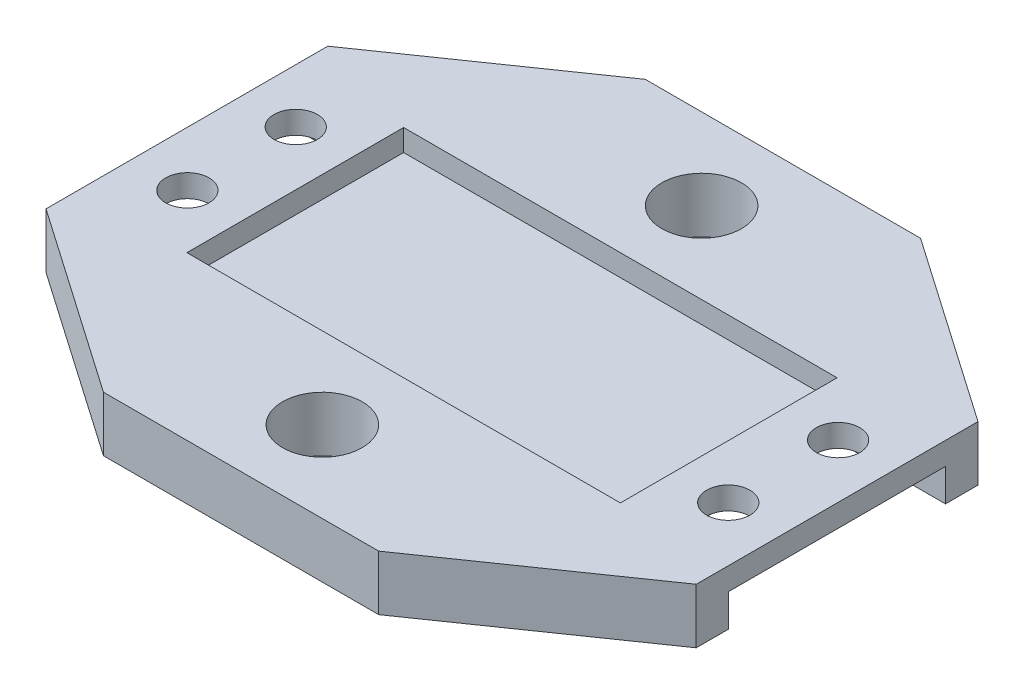
SolidWorks part; units mm, degrees
ref_plane "Front Plane" through (0, 0, 0) normal (0, 0, 1) x (1, 0, 0)
ref_plane "Top Plane" through (0, 0, 0) normal (0, 1, 0) x (1, 0, 0)
ref_plane "Right Plane" through (0, 0, 0) normal (1, 0, 0) x (0, 0, -1)
sketch "Sketch1" plane through (0, 0, 0) normal (0, 1, 0) x (1, 0, 0)
  line L0 (-48.0587, 12.2268) -> (11.9413, 12.2268) construction
  line L1 (-48.0587, 27.2268) -> (11.9413, 27.2268)
  line L2 (-48.0587, 27.2268) -> (-48.0587, -22.7732)
  line L3 (-48.0587, -22.7732) -> (11.9413, -22.7732)
  line L4 (11.9413, 27.2268) -> (11.9413, -22.7732)
  line L5 (11.9413, -7.7732) -> (-48.0587, -7.7732) construction
  line L6 (-18.0587, 27.2268) -> (-18.0587, -22.7732) construction
  dimension "D1" = 60
  dimension "D2" = 50
  dimension "D3" = 15
  dimension "D4" = 15
extrude "Boss-Extrude1" add sketch "Sketch1" along normal blind 5.08
sketch "Sketch2" plane through (0, 5.08, 0) normal (0, 1, 0) x (1, 0, 0)
  line L0 (-18.0587, 27.2268) -> (-18.0587, -22.7732) construction
  line L1 (11.9413, 27.2268) -> (-48.0587, 27.2268) construction
  line L2 (-48.0587, -22.7732) -> (11.9413, -22.7732) construction
  line L3 (-30.7587, 27.2268) -> (-5.3587, 27.2268)
  line L4 (-30.7587, 27.2268) -> (-48.0587, 15.2268)
  line L5 (-48.0587, 27.2268) -> (-48.0587, -22.7732) construction
  line L6 (-5.3587, 27.2268) -> (11.9413, 15.2268)
  line L7 (11.9413, -22.7732) -> (11.9413, 27.2268) construction
  line L8 (11.9413, 2.2268) -> (-48.0587, 2.2268) construction
  line L9 (-30.7587, -22.7732) -> (-48.0587, -10.7732)
  line L10 (-30.7587, -22.7732) -> (-5.3587, -22.7732)
  line L11 (-5.3587, -22.7732) -> (11.9413, -10.7732)
  line L12 (-48.0587, 15.2268) -> (-48.0587, -10.7732)
  line L13 (11.9413, -10.7732) -> (11.9413, 15.2268)
  circle A0 centre (-18.0587, 19.7268) radius 3.675
  circle A1 centre (-18.0587, -15.2732) radius 3.675
  point P24 (0, 0)
  dimension "D4" = 7.5
  dimension "D5" = 7.35
  dimension "D1" = 25.4
  dimension "D2" = 12
  dimension "D3" = 12
extrude "Cut-Extrude1" cut sketch "Sketch2" against normal through all flip side to cut
sketch "Sketch12" plane through (-48.0587, 0, 0) normal (-1, 0, 0) x (0, 0, 1)
  line L0 (-15.2268, 0) -> (10.7732, 0) construction
  line L1 (7.815, 0) -> (-12.185, 0)
  line L2 (7.815, 0) -> (7.815, 3)
  line L3 (7.815, 3) -> (-12.185, 3)
  line L4 (-12.185, 0) -> (-12.185, 3)
  dimension "D1" = 20
  dimension "D2" = 3
extrude "Cut-Extrude6" cut sketch "Sketch12" against normal blind 10
sketch "Sketch13" plane through (11.9413, 0, 0) normal (1, 0, 0) x (0, 0, -1)
  line L0 (-10.7732, 0) -> (15.2268, 0) construction
  line L1 (12.2268, 0) -> (-7.7732, 0)
  line L2 (12.2268, 0) -> (12.2268, 3)
  line L3 (12.2268, 3) -> (-7.7732, 3)
  line L4 (-7.7732, 0) -> (-7.7732, 3)
  dimension "D1" = 3
  dimension "D2" = 20
  dimension "D3" = 3
extrude "Cut-Extrude7" cut sketch "Sketch13" against normal blind 10
sketch "Sketch14" plane through (0, 5.08, 0) normal (0, 1, 0) x (1, 0, 0)
  line L0 (-18.0587, 27.2268) -> (-18.0587, -22.7732) construction
  line L1 (-5.3587, 27.2268) -> (-30.7587, 27.2268) construction
  line L2 (-30.7587, -22.7732) -> (-5.3587, -22.7732) construction
  line L4 (-38.0587, -7.7732) -> (1.9413, -7.7732)
  line L5 (-38.0587, -7.7732) -> (-38.0587, 12.2268)
  line L6 (-38.0587, 12.2268) -> (1.9413, 12.2268)
  line L7 (1.9413, -7.7732) -> (1.9413, 12.2268)
  line L8 (-38.0587, -7.7732) -> (1.9413, 12.2268) construction
  line L9 (-38.0587, 12.2268) -> (1.9413, -7.7732) construction
  point P6 (-18.0587, 2.2268)
  dimension "D1" = 40
  dimension "D2" = 20
extrude "Cut-Extrude8" cut sketch "Sketch14" against normal blind 2
sketch "Sketch15" plane through (0, 5.08, 0) normal (0, 1, 0) x (1, 0, 0)
  line L0 (11.9413, 2.6225) -> (-48.0587, 2.2268) construction
  line L1 (11.9413, -10.7732) -> (11.9413, 15.2268) construction
  line L2 (-48.0587, 15.2268) -> (-48.0587, -10.7732) construction
  line L3 (-18.0587, 27.2268) -> (-18.0587, -22.7732) construction
  line L4 (-5.3587, 27.2268) -> (-30.7587, 27.2268) construction
  line L5 (-30.7587, -22.7732) -> (-5.3587, -22.7732) construction
  circle A0 centre (-43.0152, -2.7732) radius 2
  circle A1 centre (-43.0816, 7.2929) radius 2
  circle A2 centre (6.9642, 7.2929) radius 2
  circle A3 centre (6.8978, -2.7732) radius 2
  dimension "D1" = 4
  dimension "D2" = 5
extrude "Cut-Extrude9" cut sketch "Sketch15" against normal through all
